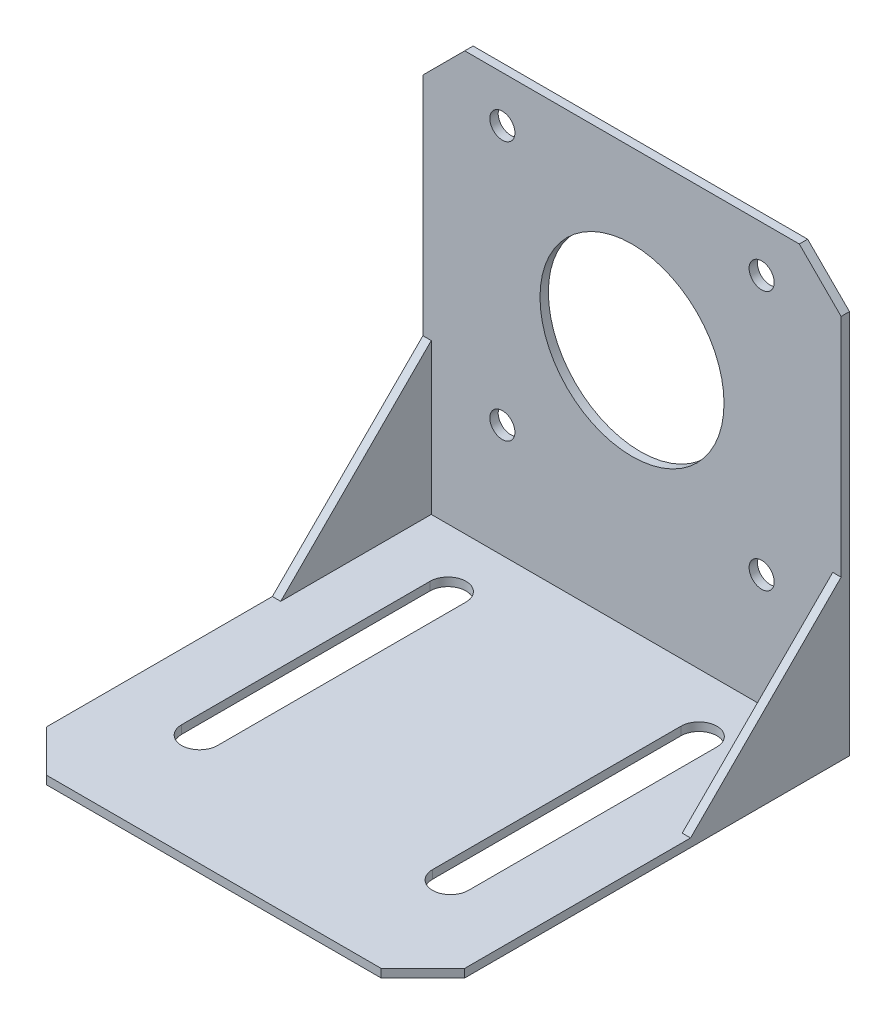
SolidWorks part; units mm, degrees
material "铸造碳钢"
ref_plane "前视基准面" through (0, 0, 0) normal (0, 0, 1) x (1, 0, 0)
ref_plane "上视基准面" through (0, 0, 0) normal (0, 1, 0) x (1, 0, 0)
ref_plane "右视基准面" through (0, 0, 0) normal (1, 0, 0) x (0, 0, -1)
sketch "草图3" plane through (0, 0, 0) normal (0, 1, 0) x (1, 0, 0)
  line L0 (-25, -20.5) -> (-20, -25.5)
  line L1 (-25, 25.5) -> (25, 25.5)
  line L2 (-25, 25.5) -> (-25, -20.5)
  line L3 (-20, -25.5) -> (20, -25.5)
  line L4 (25, 25.5) -> (25, -20.5)
  line L5 (-25, 25.5) -> (25, -25.5) construction
  line L6 (-25, -25.5) -> (25, 25.5) construction
  line L7 (20, -25.5) -> (25, -20.5)
  line L8 (-15, 17.5) -> (-15, -12.2) construction
  line L9 (-12.85, 17.5) -> (-12.85, -12.2)
  line L10 (-17.15, 17.5) -> (-17.15, -12.2)
  line L11 (15, 17.5) -> (15, -12.2) construction
  line L12 (17.15, 17.5) -> (17.15, -12.2)
  line L13 (12.85, 17.5) -> (12.85, -12.2)
  arc A0 (-12.85, 17.5) -> (-17.15, 17.5) centre (-15, 17.5) ccw
  arc A1 (-17.15, -12.2) -> (-12.85, -12.2) centre (-15, -12.2) ccw
  arc A2 (17.15, 17.5) -> (12.85, 17.5) centre (15, 17.5) ccw
  arc A3 (12.85, -12.2) -> (17.15, -12.2) centre (15, -12.2) ccw
  point P0 (0, 0)
  point P12 (-15, 2.65)
  point P17 (15, 2.65)
  dimension "D3" = 2.15
  dimension "D4" = 2.15
  dimension "D12" = 13.3
  dimension "D1" = 50
  dimension "D2" = 51
  dimension "D5" = 7.85
  dimension "D8" = 7.85
  dimension "D9" = 29.7
  dimension "D10" = 29.7
  dimension "D11" = 13.3
  dimension "D13" = 25.7
extrude "凸台-拉伸2" add sketch "草图3" along normal blind 1 contours L10 A1 L9 A0 | L13 A3 L12 A2 | L1 L4 L7 L3 L0 L2
sketch "草图4" plane through (0, 0, -25.5) normal (0, 0, -1) x (-1, 0, 0)
  line L0 (25, 0) -> (-25, 0) construction
  line L1 (-20, 51) -> (20, 51)
  line L2 (-25, 46) -> (-25, 0)
  line L3 (-25, 0) -> (25, 0)
  line L4 (25, 46) -> (25, 0)
  line L5 (25, 1) -> (25, 0) construction
  line L6 (-25, 1) -> (-25, 0) construction
  line L7 (0, 54.6493) -> (0, -9.5919) construction
  line L8 (-32.9332, 30) -> (26.3622, 30) construction
  line L9 (-25, 46) -> (-20, 51)
  line L10 (20, 51) -> (25, 46)
  circle A0 centre (0, 30) radius 11
  circle A1 centre (-15.5, 45.5) radius 1.5
  circle A2 centre (15.5, 45.5) radius 1.5
  circle A3 centre (15.5, 14.5) radius 1.5
  circle A4 centre (-15.5, 14.5) radius 1.5
  point P0 (-25, 51)
  point P3 (25, 51)
  point P8 (25, 0.5)
  dimension "D5" = 22
  dimension "D7" = 0
  dimension "D8" = 3
  dimension "D9" = 3
  dimension "D10" = 3
  dimension "D11" = 3
  dimension "D1" = 0
  dimension "D2" = 0
  dimension "D3" = 0
  dimension "D4" = 51
  dimension "D6" = 21
  dimension "D12" = 31
  dimension "D13" = 31
  dimension "D14" = 31
  dimension "D15" = 0
  dimension "D16" = 15.5
  dimension "D17" = 15.5
  dimension "D18" = 0
  dimension "D19" = 0
  dimension "D20" = 0
extrude "凸台-拉伸3" add sketch "草图4" against normal blind 1 contours A0 | L1 L10 L4 L3 L2 L9 | A1 | A2 | A3 | A4
sketch "草图5" plane through (-25, 0, 0) normal (-1, 0, 0) x (0, 0, 1)
  line L0 (-25.5, 20) -> (-25.5, 0)
  line L1 (-25.5, 46) -> (-25.5, 0) construction
  line L2 (-25.5, 0) -> (-5.5, 0)
  line L3 (-25.5, 0) -> (20.5, 0) construction
  line L4 (-5.5, 0) -> (-25.5, 20)
  dimension "D1" = 20
  dimension "D2" = 315
extrude "凸台-拉伸4" add sketch "草图5" against normal blind 1
sketch "草图6" plane through (25, 0, 0) normal (1, 0, 0) x (0, 0, -1)
  line L0 (25.5, 20) -> (25.5, 0)
  line L1 (25.5, 46) -> (25.5, 0) construction
  line L2 (25.5, 0) -> (5.5, 0)
  line L3 (25.5, 0) -> (-20.5, 0) construction
  line L4 (5.5, 0) -> (25.5, 20)
  dimension "D1" = 20
  dimension "D2" = 45
extrude "凸台-拉伸5" add sketch "草图6" against normal blind 1
